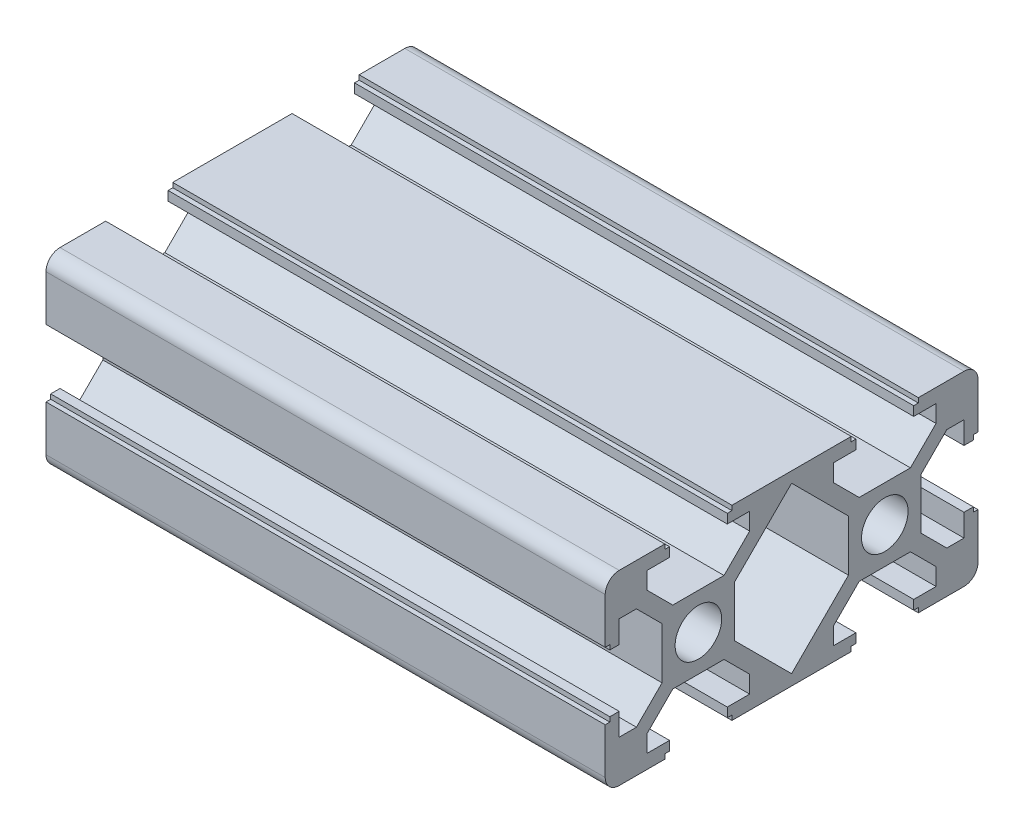
SolidWorks part; units mm, degrees
ref_plane "前视基准面" through (0, 0, 0) normal (0, 0, 1) x (1, 0, 0)
ref_plane "上视基准面" through (0, 0, 0) normal (0, 1, 0) x (1, 0, 0)
ref_plane "右视基准面" through (0, 0, 0) normal (1, 0, 0) x (0, 0, -1)
sketch "草图1" plane through (0, 0, 0) normal (0, 0, 1) x (1, 0, 0)
  line L0 (-53.3425, -1.4522) -> (6.6575, -1.4522)
other "铝型材 20X40XR1.5(2)"
ref_plane "基准面9" through (-53.3425, -1.4522, 0) normal (1, 0, 0) x (0, 1, 0)
sketch "Sketch16" plane through (-53.3425, -1.4522, 0) normal (1, 0, 0) x (0, 1, 0)
  line L0 (-3.6, 10) -> (-3.6, 9.5)
  line L1 (-3.6, 9.5) -> (-3.1, 9.5)
  line L2 (-3.1, 9.5) -> (-3.1, 8.5)
  line L3 (-3.1, 8.5) -> (-5.5, 8.5)
  line L4 (8.85, -10) -> (2.75, -3.9)
  line L5 (-10, -16.4) -> (-10, -3.6)
  line L6 (8.5, 10) -> (3.6, 10)
  line L7 (10, 8.5) -> (10, 3.6)
  line L8 (0, 14.8756) -> (0, 0) construction
  line L9 (0, 0) -> (10, 0) construction
  line L10 (-5.5, 8.5) -> (-5.5, 6.65)
  line L11 (-5.5, 6.65) -> (-2.75, 3.9)
  line L12 (-2.75, 3.9) -> (2.75, 3.9)
  line L13 (5.5, 6.65) -> (2.75, 3.9)
  line L14 (5.5, 8.5) -> (5.5, 6.65)
  line L15 (3.1, 8.5) -> (5.5, 8.5)
  line L16 (3.1, 9.5) -> (3.1, 8.5)
  line L17 (3.6, 9.5) -> (3.1, 9.5)
  line L18 (3.6, 10) -> (3.6, 9.5)
  line L19 (-3.6, 10) -> (-8.5, 10)
  line L20 (10, 3.6) -> (9.5, 3.6)
  line L21 (9.5, 3.6) -> (9.5, 3.1)
  line L22 (9.5, 3.1) -> (8.5, 3.1)
  line L23 (8.5, 3.1) -> (8.5, 5.5)
  line L24 (8.5, 5.5) -> (6.65, 5.5)
  line L25 (6.65, 5.5) -> (3.9, 2.75)
  line L26 (3.9, 2.75) -> (3.9, -2.75)
  line L27 (6.65, -5.5) -> (3.9, -2.75)
  line L28 (8.5, -5.5) -> (6.65, -5.5)
  line L29 (8.5, -3.1) -> (8.5, -5.5)
  line L30 (9.5, -3.1) -> (8.5, -3.1)
  line L31 (9.5, -3.6) -> (9.5, -3.1)
  line L32 (10, -3.6) -> (9.5, -3.6)
  line L33 (8.85, -10) -> (2.75, -16.1)
  line L34 (-8.85, -10) -> (-2.75, -16.1)
  line L35 (-8.85, -10) -> (-2.75, -3.9)
  line L39 (2.75, -3.9) -> (-2.75, -3.9)
  line L46 (-10, -3.6) -> (-9.5, -3.6)
  line L47 (-9.5, -3.6) -> (-9.5, -3.1)
  line L48 (-9.5, -3.1) -> (-8.5, -3.1)
  line L49 (-8.5, -3.1) -> (-8.5, -5.5)
  line L50 (-8.5, -5.5) -> (-6.65, -5.5)
  line L51 (-6.65, -5.5) -> (-3.9, -2.75)
  line L52 (-3.9, -2.75) -> (-3.9, 2.75)
  line L53 (-6.65, 5.5) -> (-3.9, 2.75)
  line L54 (-8.5, 5.5) -> (-6.65, 5.5)
  line L55 (-8.5, 3.1) -> (-8.5, 5.5)
  line L56 (-9.5, 3.1) -> (-8.5, 3.1)
  line L57 (-9.5, 3.6) -> (-9.5, 3.1)
  line L58 (-10, 3.6) -> (-9.5, 3.6)
  line L60 (-10, 3.6) -> (-10, 8.5)
  line L61 (10, -3.6) -> (10, -16.4)
  line L66 (-8.5, -30) -> (-3.6, -30)
  line L67 (-10, -28.5) -> (-10, -23.6)
  line L72 (-2.75, -16.1) -> (2.75, -16.1)
  line L80 (10, -16.4) -> (9.5, -16.4)
  line L81 (9.5, -16.4) -> (9.5, -16.9)
  line L82 (9.5, -16.9) -> (8.5, -16.9)
  line L83 (8.5, -16.9) -> (8.5, -14.5)
  line L84 (8.5, -14.5) -> (6.65, -14.5)
  line L85 (6.65, -14.5) -> (3.9, -17.25)
  line L86 (3.9, -17.25) -> (3.9, -22.75)
  line L87 (6.65, -25.5) -> (3.9, -22.75)
  line L88 (8.5, -25.5) -> (6.65, -25.5)
  line L89 (8.5, -23.1) -> (8.5, -25.5)
  line L90 (9.5, -23.1) -> (8.5, -23.1)
  line L91 (9.5, -23.6) -> (9.5, -23.1)
  line L92 (10, -23.6) -> (9.5, -23.6)
  line L93 (3.6, -30) -> (3.6, -29.5)
  line L94 (3.6, -29.5) -> (3.1, -29.5)
  line L95 (3.1, -29.5) -> (3.1, -28.5)
  line L96 (3.1, -28.5) -> (5.5, -28.5)
  line L97 (5.5, -28.5) -> (5.5, -26.65)
  line L98 (5.5, -26.65) -> (2.75, -23.9)
  line L99 (2.75, -23.9) -> (-2.75, -23.9)
  line L100 (-5.5, -26.65) -> (-2.75, -23.9)
  line L101 (-5.5, -28.5) -> (-5.5, -26.65)
  line L102 (-3.1, -28.5) -> (-5.5, -28.5)
  line L103 (-3.1, -29.5) -> (-3.1, -28.5)
  line L104 (-3.6, -29.5) -> (-3.1, -29.5)
  line L105 (-3.6, -30) -> (-3.6, -29.5)
  line L106 (-10, -23.6) -> (-9.5, -23.6)
  line L107 (-9.5, -23.6) -> (-9.5, -23.1)
  line L108 (-9.5, -23.1) -> (-8.5, -23.1)
  line L109 (-8.5, -23.1) -> (-8.5, -25.5)
  line L110 (-8.5, -25.5) -> (-6.65, -25.5)
  line L111 (-6.65, -25.5) -> (-3.9, -22.75)
  line L112 (-3.9, -22.75) -> (-3.9, -17.25)
  line L113 (-6.65, -14.5) -> (-3.9, -17.25)
  line L114 (-8.5, -14.5) -> (-6.65, -14.5)
  line L115 (-8.5, -16.9) -> (-8.5, -14.5)
  line L116 (-9.5, -16.9) -> (-8.5, -16.9)
  line L117 (-9.5, -16.4) -> (-9.5, -16.9)
  line L118 (-10, -16.4) -> (-9.5, -16.4)
  line L119 (3.6, -30) -> (8.5, -30)
  line L121 (10, -23.6) -> (10, -28.5)
  line L122 (0, -20) -> (10, -20) construction
  line L125 (3.6, -10) -> (3.6, -9.5) [skipped]
  line L127 (3.6, -9.5) -> (3.1, -9.5) [skipped]
  line L129 (3.1, -9.5) -> (3.1, -8.5) [skipped]
  line L131 (3.1, -8.5) -> (5.5, -8.5) [skipped]
  line L133 (-3.1, -8.5) -> (-5.5, -8.5) [skipped]
  line L135 (-3.1, -9.5) -> (-3.1, -8.5) [skipped]
  line L137 (-3.6, -9.5) -> (-3.1, -9.5) [skipped]
  line L139 (-3.6, -10) -> (-3.6, -9.5) [skipped]
  line L141 (-3.6, -10) -> (-3.6, -10.5) [skipped]
  line L142 (-3.6, -10.5) -> (-3.1, -10.5) [skipped]
  line L143 (-3.1, -10.5) -> (-3.1, -11.5) [skipped]
  line L144 (-3.1, -11.5) -> (-5.5, -11.5) [skipped]
  line L145 (8.5, -10) -> (3.6, -10) [skipped]
  line L146 (3.1, -11.5) -> (5.5, -11.5) [skipped]
  line L147 (3.1, -10.5) -> (3.1, -11.5) [skipped]
  line L148 (3.6, -10.5) -> (3.1, -10.5) [skipped]
  line L149 (3.6, -10) -> (3.6, -10.5) [skipped]
  line L150 (-3.6, -10) -> (-8.5, -10) [skipped]
  line L151 (-10, -16.4) -> (-10, -11.5) [skipped]
  line L152 (10, -11.5) -> (10, -16.4) [skipped]
  line L154 (-5.5, -8.5) -> (-5.5, -6.65) [skipped]
  line L156 (5.5, -8.5) -> (5.5, -6.65) [skipped]
  line L157 (5.5, -11.5) -> (5.5, -13.35) [skipped]
  line L158 (-5.5, -11.5) -> (-5.5, -13.35) [skipped]
  line L160 (-12.2446, -13.3946) -> (-10, -11.15) [skipped]
  line L161 (13.644, -5.206) -> (10, -8.85) [skipped]
  line L163 (12.1963, -13.3463) -> (10, -11.15) [skipped]
  line L164 (-11.1344, -7.7156) -> (-10, -8.85) [skipped]
  circle A0 centre (0, 0) radius 2.5
  arc A1 (-10, 8.5) -> (-8.5, 10) centre (-8.5, 8.5) cw
  arc A2 (10, 8.5) -> (8.5, 10) centre (8.5, 8.5) ccw
  arc A3 (10, -28.5) -> (8.5, -30) centre (8.5, -28.5) cw
  arc A4 (-10, -28.5) -> (-8.5, -30) centre (-8.5, -28.5) ccw
  circle A5 centre (0, -20) radius 2.5
  arc A12 (-10, -11.5) -> (-8.5, -10) centre (-8.5, -11.5) cw [skipped]
  arc A13 (10, -11.5) -> (8.5, -10) centre (8.5, -11.5) ccw [skipped]
  point P0 (-10, 0)
  point P1 (10, 0)
  point P2 (0, 10)
  point P4 (0, 0)
  point P5 (0, -10)
  point P6 (-10, -10)
  point P7 (10, 10)
  point P8 (-10, 10)
  point P12 (-10, -10)
  point P13 (10, -10)
  point P15 (0, -10)
  point P16 (10, -10)
  point P36 (-10, 10)
  point P39 (10, 10)
  point P43 (-10, -20)
  point P44 (10, -20)
  point P62 (0, 0)
  point P88 (0, -30)
  point P89 (0, -20)
  point P90 (-10, -30)
  point P91 (10, -30)
  dimension "D1" = 11
  dimension "D2" = 20
  dimension "D3" = 6.2
  dimension "D4" = 7.2
  dimension "D5" = 6.1
  dimension "D6" = 5
  dimension "D7" = 1.5
  dimension "D8" = 45
  dimension "D14" = 20
  dimension "D15" = 1.5
  dimension "D9" = 0.5
  dimension "D10" = 1
  dimension "D11" = 5.5
  dimension "D12" = 10
  dimension "D13" = 40
  dimension "D16" = 45
  dimension "D17" = 45
  dimension "D18" = 45
  dimension "D19" = 6.2
